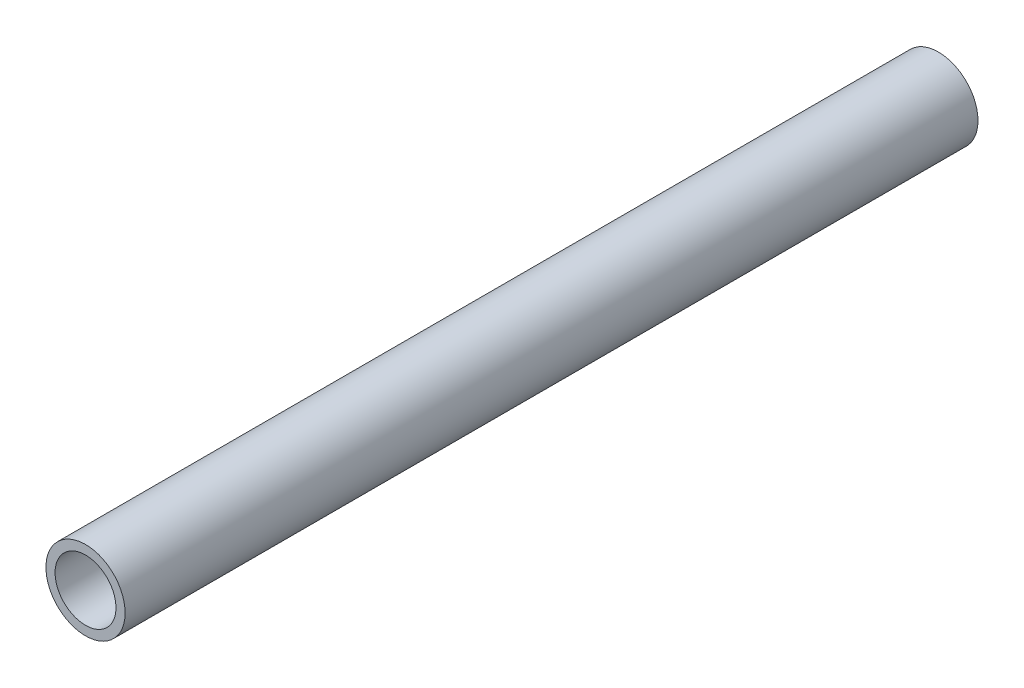
SolidWorks part; units mm, degrees
ref_plane "Front Plane" through (0, 0, 0) normal (0, 0, 1) x (1, 0, 0)
ref_plane "Top Plane" through (0, 0, 0) normal (0, 1, 0) x (1, 0, 0)
ref_plane "Right Plane" through (0, 0, 0) normal (1, 0, 0) x (0, 0, -1)
sketch "Sketch1" plane through (0, 0, 0) normal (0, 0, 1) x (1, 0, 0)
  circle A0 centre (0, 0) radius 16.51
  dimension "D1" = 33.02
extrude "Boss-Extrude1" add sketch "Sketch1" along normal blind 355.6 contours A0
sketch "Sketch2" plane through (0, 0, 0) normal (0, 0, -1) x (-1, 0, 0)
  circle A0 centre (0, 0) radius 12.7
  dimension "D1" = 25.4
extrude "Cut-Extrude1" cut sketch "Sketch2" against normal blind 355.6 contours A0
